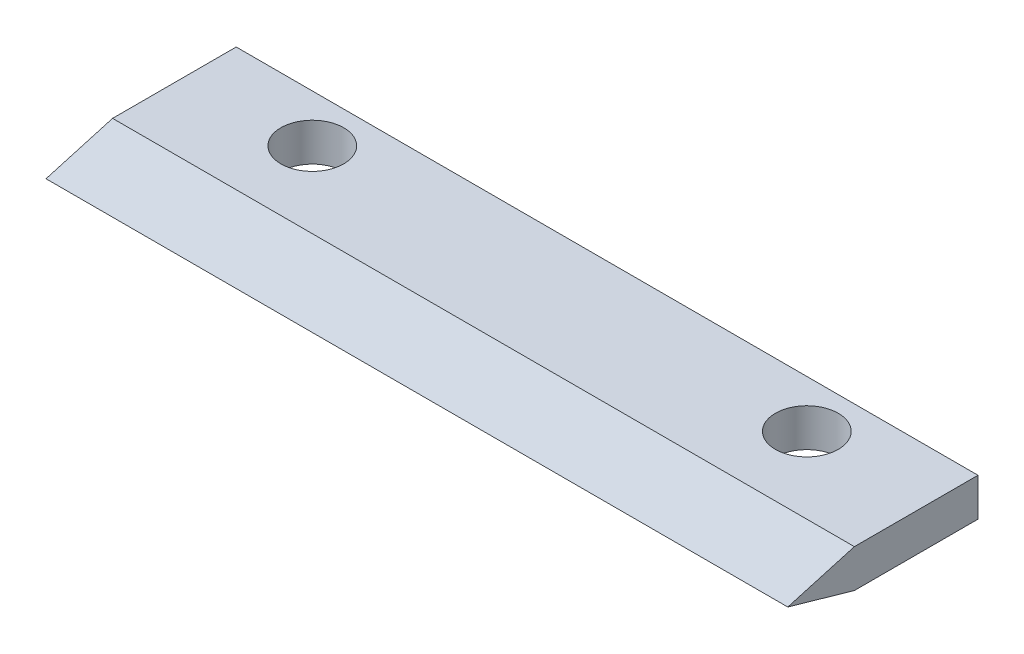
SolidWorks part; units mm, degrees
material "AISI 类型 A2 刀具钢"
ref_plane "前视基准面" through (0, 0, 0) normal (0, 0, 1) x (1, 0, 0)
ref_plane "上视基准面" through (0, 0, 0) normal (0, 1, 0) x (1, 0, 0)
ref_plane "右视基准面" through (0, 0, 0) normal (1, 0, 0) x (0, 0, -1)
sketch "草图1" plane through (0, 0, 0) normal (0, 1, 0) x (1, 0, 0)
  line L1 (0, 0) -> (39, 0)
  line L2 (0, 0) -> (0, 10)
  line L3 (0, 10) -> (39, 10)
  line L4 (39, 0) -> (39, 10)
  circle A0 centre (6.5, 7.5) radius 1.65
  circle A1 centre (32.5, 7.5) radius 1.65
  dimension "D7" = 3.3
  dimension "D3" = 3.3
  dimension "D4" = 6.5
  dimension "D5" = 6.5
  dimension "D1" = 26
  dimension "D2" = 10
  dimension "D8" = 2.5
extrude "凸台-拉伸1" add sketch "草图1" along normal blind 2
sketch "草图2" plane through (39, 0, 0) normal (1, 0, 0) x (0, 0, -1)
  line L0 (3.5, 2) -> (0, 2)
  line L1 (0, 2) -> (10, 2) construction
  line L2 (0, 2) -> (0, 1)
  line L3 (0, 2) -> (0, 0) construction
  line L4 (0, 1) -> (3.5, 2)
  dimension "D1" = 3.5
extrude "切除-拉伸1" cut sketch "草图2" against normal blind 42
sketch "草图3" plane through (39, 0, 0) normal (1, 0, 0) x (0, 0, -1)
  line L0 (0, 1) -> (0, 0)
  line L1 (0, 0) -> (3.5, 0)
  line L2 (0, 0) -> (10, 0) construction
  line L3 (3.5, 0) -> (0, 1)
  dimension "D1" = 3.5
extrude "切除-拉伸2" cut sketch "草图3" against normal blind 42
